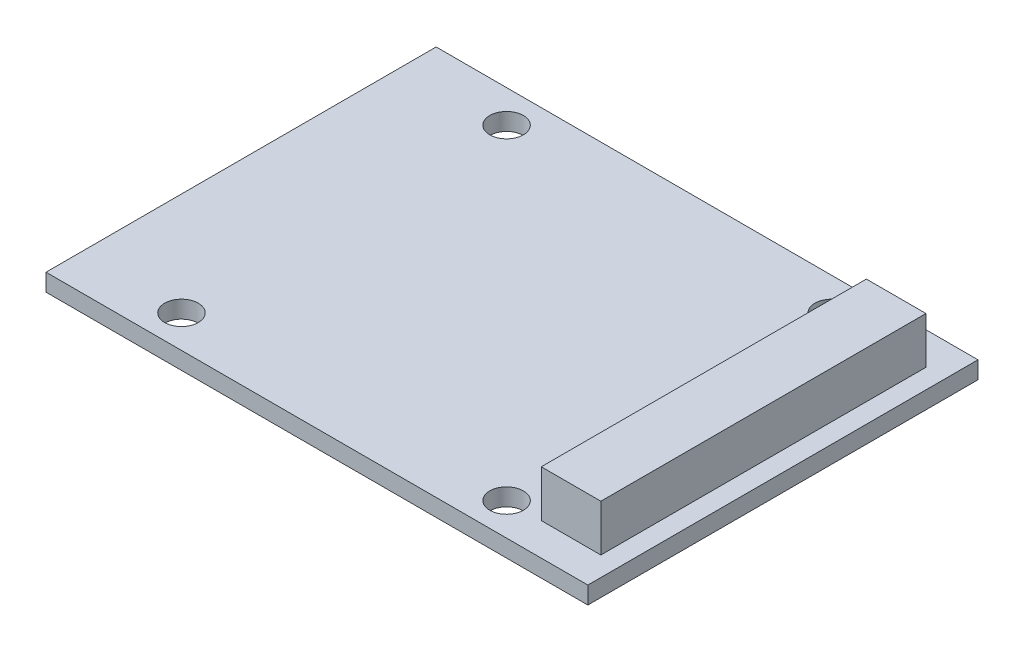
SolidWorks part; units mm, degrees
ref_plane "Front Plane" through (0, 0, 0) normal (0, 0, 1) x (1, 0, 0)
ref_plane "Top Plane" through (0, 0, 0) normal (0, 1, 0) x (1, 0, 0)
ref_plane "Right Plane" through (0, 0, 0) normal (1, 0, 0) x (0, 0, -1)
sketch "Sketch1" plane through (0, 0, 0) normal (0, 1, 0) x (1, 0, 0)
  line L0 (-25, 0) -> (25, 0) construction
  line L1 (25, 18) -> (-25, 18)
  line L2 (25, 18) -> (25, -18)
  line L3 (25, -18) -> (-25, -18)
  line L4 (-25, 18) -> (-25, -18)
  line L5 (25, 18) -> (-25, -18) construction
  line L6 (25, -18) -> (-25, 18) construction
  circle A0 centre (-15.5, 15) radius 1.55
  circle A1 centre (-15.5, -15) radius 1.55
  circle A2 centre (14.5, 15) radius 1.55
  circle A3 centre (14.5, -15) radius 1.55
  point P0 (0, 0)
  dimension "D3" = 3.1
  dimension "D1" = 50
  dimension "D2" = 36
  dimension "D4" = 9.5
  dimension "D5" = 3
  dimension "D6" = 10.5
extrude "Boss-Extrude1" add sketch "Sketch1" along normal blind 1.6
sketch "Sketch2" plane through (0, 1.6, 0) normal (0, 1, 0) x (1, 0, 0)
  line L0 (23.2, 0) -> (17.7, 0) construction
  line L1 (23.2, 15) -> (17.7, 15)
  line L2 (23.2, 15) -> (23.2, -15)
  line L3 (23.2, -15) -> (17.7, -15)
  line L4 (17.7, 15) -> (17.7, -15)
  line L5 (25, 0) -> (-25, 0) construction
  line L6 (25, -18) -> (25, 18) construction
  line L7 (-25, 18) -> (-25, -18) construction
  dimension "D1" = 5.5
  dimension "D2" = 30
  dimension "D3" = 1.8
extrude "Boss-Extrude2" add sketch "Sketch2" along normal blind 4.3
